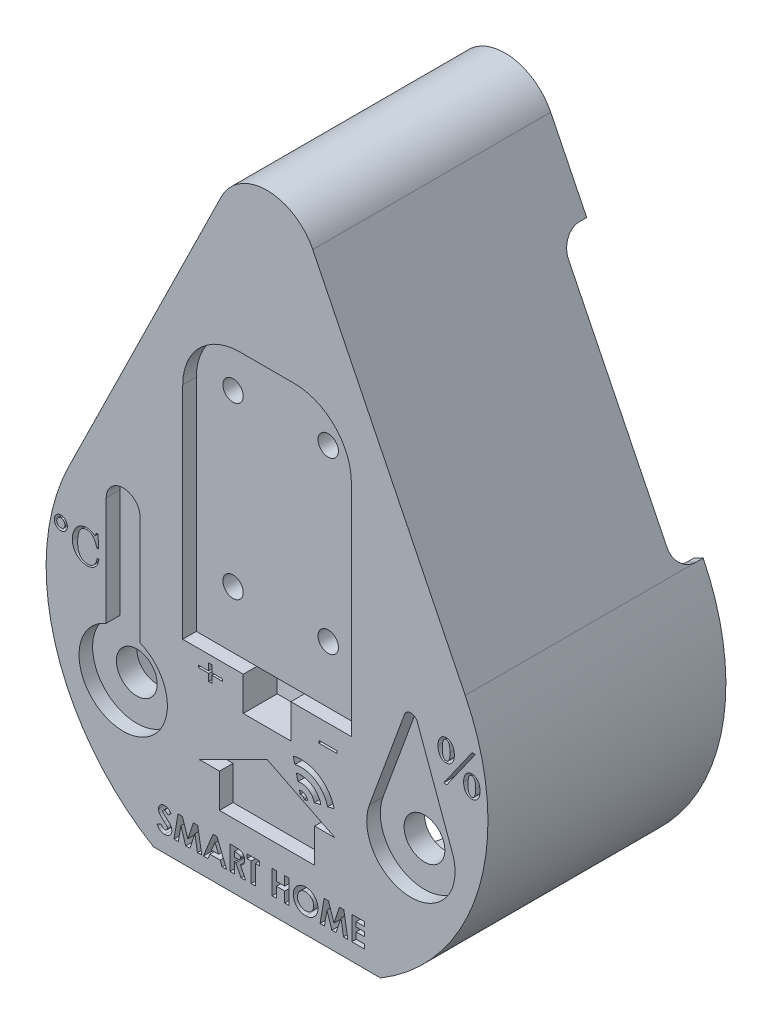
SolidWorks part; units mm, degrees
ref_plane "Plan de face" through (0, 0, 0) normal (0, 0, 1) x (1, 0, 0)
ref_plane "Plan de dessus" through (0, 0, 0) normal (0, 1, 0) x (1, 0, 0)
ref_plane "Plan de droite" through (0, 0, 0) normal (1, 0, 0) x (0, 0, -1)
sketch "Esquisse2" plane through (0, 0, 0) normal (0, 0, 1) x (1, 0, 0)
  line L0 (-26.9176, 13.2455) -> (-4.4863, 58.8304) construction
  line L1 (4.4863, 58.8304) -> (26.9176, 13.2455) construction
  line L2 (-16, -25.3772) -> (16, -25.3772) construction
  line L3 (-29.1607, 14.3493) -> (-6.7294, 59.9342)
  line L4 (6.7294, 59.9342) -> (29.1607, 14.3493)
  line L5 (-16.7067, -27.8772) -> (16.7067, -27.8772)
  arc A0 (-26.9176, 13.2455) -> (-16, -25.3772) centre (0, 0) ccw construction
  arc A1 (16, -25.3772) -> (26.9176, 13.2455) centre (0, 0) ccw construction
  arc A2 (-4.4863, 58.8304) -> (4.4863, 58.8304) centre (0, 56.6228) cw construction
  arc A3 (-6.7294, 59.9342) -> (6.7294, 59.9342) centre (0, 56.6228) cw
  arc A4 (16.7067, -27.8772) -> (29.1607, 14.3493) centre (0, 0) ccw
  arc A5 (-29.1607, 14.3493) -> (-16.7067, -27.8772) centre (0, 0) ccw
  point P13 (0, 67.9474)
  dimension "D1" = 5
  dimension "D2" = 30
  dimension "D3" = 2.5
  dimension "D5" = 32
  dimension "D6" = 82
extrude "Boss.-Extru.1" add sketch "Esquisse2" against normal blind 35
shell "Coque1" thickness 1.5
sketch "Esquisse3" plane through (-29.1607, 14.3493, 0) normal (-0.8973, 0.4415, 0) x (0, 0, 1)
  line L0 (-35, 38.805) -> (-31, 38.805)
  line L1 (-35, 50.805) -> (-35, 0) construction
  line L2 (-31, 38.805) -> (-31, 0)
  line L3 (-31, 0) -> (-35, 0)
  line L4 (-35, 50.805) -> (0, 50.805) construction
  line L5 (-35, 38.805) -> (-35, 0)
  dimension "D1" = 12
  dimension "D2" = 4
extrude "Enlèv. mat.-Extru.1" cut sketch "Esquisse3" against normal blind 15
mirror "Symétrie1" about plane through (0, 0, 0) normal (1, 0, 0) of "Enlèv. mat.-Extru.1"
fillet "Congé1" radius 3 4 edges at (11.3547, 48.8361, -31) (28.4878, 14.0182, -31) (-28.4878, 14.0182, -31) (-11.3547, 48.8361, -31)
sketch "Esquisse4" plane through (0, 0, 0) normal (0, 0, 1) x (1, 0, 0)
  line L0 (0, -34.5528) -> (0, 75.244) construction
  circle A0 centre (-8, 40.6228) radius 1.35
  arc A1 (6.7294, 59.9342) -> (-6.7294, 59.9342) centre (0, 56.6228) ccw construction
  circle A2 centre (8, 40.6228) radius 1.35
  circle A3 centre (26, 3.6228) radius 1.35
  circle A4 centre (-26, 3.6228) radius 1.35
  dimension "D3" = 37
  dimension "D4" = 2.7
  dimension "D2" = 8
  dimension "D1" = 16
  dimension "D5" = 26
extrude "Boss.-Extru.2" add sketch "Esquisse4" against normal blind 30
sketch "Esquisse5" plane through (0, -27.8772, 0) normal (0, -1, 0) x (1, 0, 0)
  line L0 (-5, -35) -> (-5, -18)
  line L1 (-16.7067, -35) -> (16.7067, -35) construction
  line L2 (-5, -18) -> (5, -18)
  line L3 (5, -18) -> (5, -35)
  line L4 (5, -35) -> (-5, -35)
  point P7 (0, -18)
  dimension "D1" = 10
  dimension "D2" = 17
extrude "Enlèv. mat.-Extru.2" cut sketch "Esquisse5" against normal up to next
fillet "Congé2" radius 3 2 edges at (5, -27.1272, -18) (-5, -27.1272, -18)
sketch "Esquisse6" plane through (0, 0, 0) normal (0, 0, 1) x (1, 0, 0)
  line L0 (-12, 1.1228) -> (12, 1.1228) construction
  line L1 (12, 1.1228) -> (12, 33.1228) construction
  line L2 (4, 41.1228) -> (-4, 41.1228) construction
  line L3 (-12, 33.1228) -> (-12, 1.1228) construction
  line L4 (-16.7067, -27.8772) -> (16.7067, -27.8772) construction
  line L5 (-12.4, 33.1228) -> (-12.4, 0.7228)
  line L6 (-12.4, 0.7228) -> (12.4, 0.7228)
  line L7 (12.4, 0.7228) -> (12.4, 33.1228)
  line L8 (4, 41.5228) -> (-4, 41.5228)
  arc A0 (12, 33.1228) -> (4, 41.1228) centre (4, 33.1228) ccw construction
  arc A1 (-4, 41.1228) -> (-12, 33.1228) centre (-4, 33.1228) ccw construction
  arc A2 (12.4, 33.1228) -> (4, 41.5228) centre (4, 33.1228) ccw
  arc A3 (-4, 41.5228) -> (-12.4, 33.1228) centre (-4, 33.1228) ccw
  text T0 "+" font "Century Gothic" height 3.5
  text T1 "-" font "Century Gothic" height 3.5
  point P3 (0, 1.1228)
  point P12 (12, 41.1228)
  dimension "D4" = 8
  dimension "D1" = 29
  dimension "D2" = 24
  dimension "D3" = 40
  dimension "D5" = 0.4
extrude "Enlèv. mat.-Extru.3" cut sketch "Esquisse6" against normal blind 2
sketch "Esquisse7" plane through (0, 0, 0) normal (0, 0, 1) x (1, 0, 0)
  line L0 (-3.5, 0.7228) -> (-3.5, -4.2772)
  line L1 (-12.4, 0.7228) -> (12.4, 0.7228) construction
  line L2 (-3.5, -4.2772) -> (3.5, -4.2772)
  line L3 (3.5, -4.2772) -> (3.5, 0.7228)
  line L4 (3.5, 0.7228) -> (-3.5, 0.7228)
  point P4 (0, 0.7228)
  dimension "D1" = 7
  dimension "D2" = 5
extrude "Enlèv. mat.-Extru.4" cut sketch "Esquisse7" against normal up to next
sketch "Esquisse8" plane through (0, 0, 0) normal (0, 0, 1) x (1, 0, 0)
  line L0 (12.4, 0.7228) -> (12.4, 33.1228) construction
  line L2 (0, -11.9557) -> (0, 44.346) construction
  line L3 (4, 41.5228) -> (-4, 41.5228) construction
  circle A0 centre (7, 34.1228) radius 1.5
  circle A2 centre (-7, 34.1228) radius 1.5
  circle A3 centre (-7, 9.1228) radius 1.5
  circle A4 centre (7, 9.1228) radius 1.5
  dimension "D2" = 7.4
  dimension "D3" = 3
  dimension "D1" = 5.4
  dimension "D4" = 2
extrude "Enlèv. mat.-Extru.5" cut sketch "Esquisse8" against normal up to next
sketch "Esquisse9" plane through (0, 0, 0) normal (0, 0, 1) x (1, 0, 0)
  line L0 (-16.7067, -27.8772) -> (16.7067, -27.8772) construction
  line L1 (0, -48.6617) -> (0, 54.9706) construction
  circle A0 centre (-21.1607, -8.8772) radius 3
  circle A3 centre (21.1607, -8.8772) radius 3
  dimension "D2" = 8
  dimension "D3" = 6
  dimension "D1" = 19
extrude "Enlèv. mat.-Extru.6" cut sketch "Esquisse9" against normal up to next
sketch "Esquisse10" plane through (0, 0, 0) normal (0, 0, 1) x (1, 0, 0)
  line L0 (15.0568, -6.6428) -> (20.2216, 7.4666)
  line L1 (22.0998, 7.4666) -> (27.2646, -6.6428)
  line L2 (-23.6607, -2.8772) -> (-23.6607, 13.1228)
  line L3 (-18.6607, 13.1228) -> (-18.6607, -2.8772)
  line L4 (0, -46.2983) -> (0, 68.7714) construction
  line L5 (-7, -18.3772) -> (7, -18.3772)
  line L6 (7, -18.3772) -> (7, -13.3772)
  line L7 (7, -13.3772) -> (10, -13.3772)
  line L8 (10, -13.3772) -> (0, -8.3772)
  line L9 (-7, -18.3772) -> (-7, -13.3772)
  line L10 (-7, -13.3772) -> (-10, -13.3772)
  line L11 (-10, -13.3772) -> (0, -8.3772)
  line L12 (-16.7067, -27.8772) -> (16.7067, -27.8772) construction
  line L13 (5.4868, -10.7631) -> (5.9736, -10.649)
  line L14 (4.8859, -10.3903) -> (4.7718, -9.9035)
  line L15 (5, -10.8772) -> (7.6355, -6.6281) construction
  line L16 (8.8945, -9.9644) -> (9.8681, -9.7362)
  line L17 (4.0872, -6.9827) -> (3.859, -6.0091)
  line L18 (6.9472, -10.4208) -> (7.9208, -10.1926)
  line L19 (4.5436, -8.9299) -> (4.3154, -7.9563)
  arc A0 (27.2646, -6.6428) -> (15.0568, -6.6428) centre (21.1607, -8.8772) cw
  arc A1 (20.2216, 7.4666) -> (22.0998, 7.4666) centre (21.1607, 7.1228) cw
  arc A2 (-23.6607, -2.8772) -> (-18.6607, -2.8772) centre (-21.1607, -8.8772) ccw
  arc A3 (-23.6607, 13.1228) -> (-18.6607, 13.1228) centre (-21.1607, 13.1228) cw
  arc A4 (3.859, -6.0091) -> (9.8681, -9.7362) centre (5, -10.8772) cw
  arc A5 (4.0872, -6.9827) -> (8.8945, -9.9644) centre (5, -10.8772) cw
  arc A6 (4.3154, -7.9563) -> (7.9208, -10.1926) centre (5, -10.8772) cw
  arc A7 (4.5436, -8.9299) -> (6.9472, -10.4208) centre (5, -10.8772) cw
  arc A8 (4.7718, -9.9035) -> (5.9736, -10.649) centre (5, -10.8772) cw
  arc A9 (4.8859, -10.3903) -> (5.4868, -10.7631) centre (5, -10.8772) cw
  text T0 "%" font "Century Schoolbook" height in points 24
  text T1 "°C" font "Century Schoolbook" height in points 18
  text T2 "<b>SMART HOME</b>"
  point P9 (25.6607, 5.1228)
  point P30 (5, -10.8772)
  point P33 (0, -18.3772)
  dimension "D1" = 6.5
  dimension "D2" = 1
  dimension "D4" = 13
  dimension "D6" = 2.5
  dimension "D21" = 5
  dimension "D3" = 16
  dimension "D5" = 22
  dimension "D7" = 14
  dimension "D8" = 4.5
  dimension "D9" = 10.5
  dimension "D10" = 4.5
  dimension "D11" = 10
  dimension "D12" = 8
  dimension "D13" = 7
  dimension "D14" = 5
  dimension "D15" = 3
  dimension "D16" = 10
  dimension "D17" = 9.5
  dimension "D18" = 2.5
  dimension "D19" = 33
  dimension "D20" = 13.191
  dimension "D22" = 1
  dimension "D23" = 1
  dimension "D24" = 1
  dimension "D25" = 1
  dimension "D26" = 0.5
extrude "Enlèv. mat.-Extru.7" cut sketch "Esquisse10" against normal blind 2
sketch "Esquisse11" plane through (0, -27.8772, 0) normal (0, -1, 0) x (1, 0, 0)
  line L0 (-16.7067, 0) -> (16.7067, 0) construction
  line L1 (-16.7067, -35) -> (-16.7067, 0) construction
  text T0 "<b>POWER</b>"
  dimension "D1" = 10
  dimension "D2" = 8
extrude "Enlèv. mat.-Extru.10" cut sketch "Esquisse11" against normal up to next
